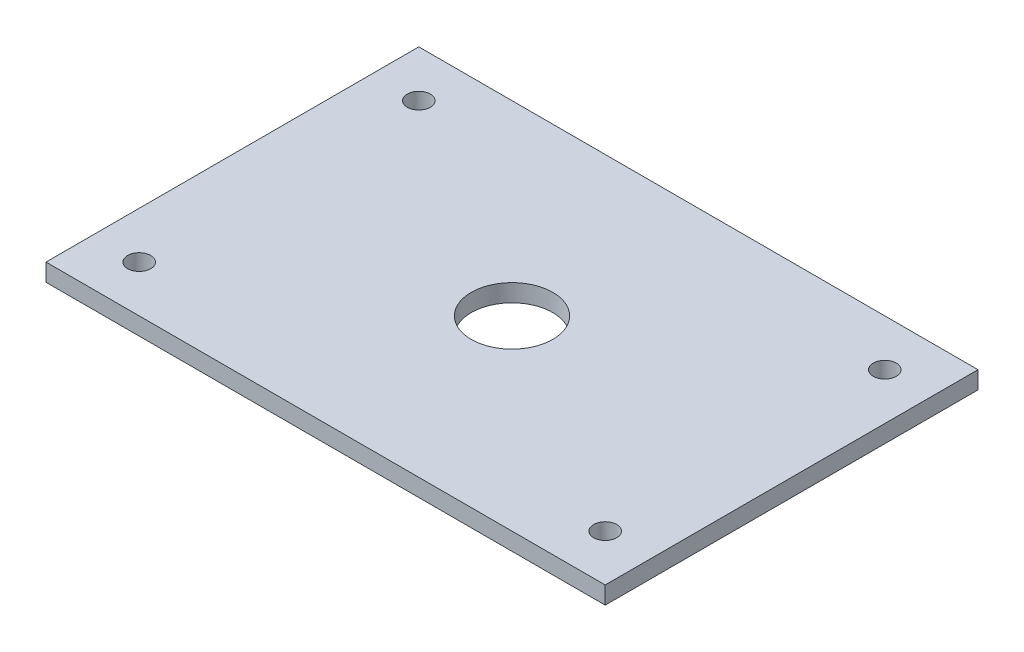
SolidWorks part; units mm, degrees
material "6063-T5"
ref_plane "Front Plane" through (0, 0, 0) normal (0, 0, 1) x (1, 0, 0)
ref_plane "Top Plane" through (0, 0, 0) normal (0, 1, 0) x (1, 0, 0)
ref_plane "Right Plane" through (0, 0, 0) normal (1, 0, 0) x (0, 0, -1)
sketch "Sketch1" plane through (0, 0, 0) normal (0, 1, 0) x (1, 0, 0)
  line L1 (-57.436, 29.2901) -> (94.964, 29.2901)
  line L2 (-57.436, 29.2901) -> (-57.436, -72.3099)
  line L3 (-57.436, -72.3099) -> (94.964, -72.3099)
  line L4 (94.964, 29.2901) -> (94.964, -72.3099)
  dimension "D1" = 152.4
  dimension "D2" = 101.6
extrude "Boss-Extrude1" add sketch "Sketch1" along normal blind 4.7752
sketch "Sketch2" plane through (0, 4.7752, 0) normal (0, 1, 0) x (1, 0, 0)
  line L0 (94.964, 29.2901) -> (-57.436, 29.2901) construction
  line L1 (-57.436, 29.2901) -> (-57.436, -72.3099) construction
  line L2 (94.964, -72.3099) -> (94.964, 29.2901) construction
  circle A0 centre (-44.736, 16.5901) radius 3.1369
  circle A1 centre (82.264, 16.5901) radius 3.1369
  circle A2 centre (82.264, -59.6099) radius 3.1369
  circle A3 centre (-44.736, -59.6099) radius 3.1369
  circle A4 centre (18.764, -21.5099) radius 11.1125
  dimension "D3" = 2
  dimension "D1" = 12.7
  dimension "D2" = 12.7
  dimension "D5" = 76.2
  dimension "D6" = 50.8
  dimension "D4" = 2
extrude "Cut-Extrude1" cut sketch "Sketch2" against normal blind 4.7752
